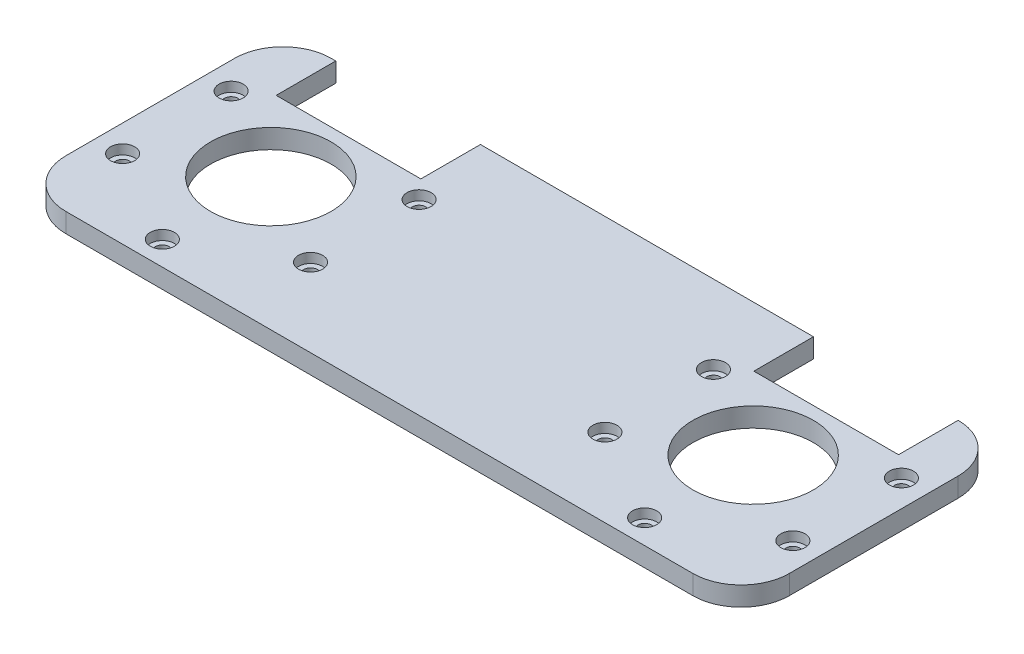
SolidWorks part; units mm, degrees
ref_plane "Front Plane" through (0, 0, 0) normal (0, 0, 1) x (1, 0, 0)
ref_plane "Top Plane" through (0, 0, 0) normal (0, 1, 0) x (1, 0, 0)
ref_plane "Right Plane" through (0, 0, 0) normal (1, 0, 0) x (0, 0, -1)
sketch "Sketch1" plane through (0, 0, 0) normal (0, 1, 0) x (1, 0, 0)
  line L0 (-50, 0) -> (50, 0) construction
  line L1 (-75, 27.5) -> (75, 27.5)
  line L2 (-75, 27.5) -> (-75, -27.5)
  line L3 (-75, -27.5) -> (75, -27.5)
  line L4 (75, 27.5) -> (75, -27.5)
  line L5 (0, 27.5) -> (0, 0) construction
  line L6 (0, 0) -> (0, -27.5) construction
  circle A0 centre (-50, 0) radius 12.5
  circle A1 centre (50, 0) radius 12.5
  dimension "D1" = 55
  dimension "D4" = 25
  dimension "D2" = 150
  dimension "D3" = 100
extrude "Boss-Extrude1" add sketch "Sketch1" along normal blind 4
sketch "Sketch2" plane through (0, 4, 0) normal (0, 1, 0) x (1, 0, 0)
  arc A0 (30.5144, -10.225) -> (30.5144, -12.275) centre (30.5144, -11.25) ccw construction
  arc A1 (30.5144, -10.225) -> (30.5144, -12.275) centre (30.5144, -11.25) ccw construction
  arc A2 (69.4856, -12.275) -> (69.4856, -10.225) centre (69.4856, -11.25) ccw construction
  arc A3 (69.4856, 10.225) -> (69.4856, 12.275) centre (69.4856, 11.25) ccw construction
  arc A4 (30.5144, 12.275) -> (30.5144, 10.225) centre (30.5144, 11.25) ccw construction
  arc A5 (50, -21.475) -> (50, -23.525) centre (50, -22.5) ccw construction
  arc A6 (69.4856, -12.275) -> (69.4856, -10.225) centre (69.4856, -11.25) ccw construction
  arc A7 (69.4856, 10.225) -> (69.4856, 12.275) centre (69.4856, 11.25) ccw construction
  arc A8 (30.5144, 12.275) -> (30.5144, 10.225) centre (30.5144, 11.25) ccw construction
  arc A9 (50, -21.475) -> (50, -23.525) centre (50, -22.5) ccw construction
  circle A10 centre (30.5144, 11.25) radius 1.4
  circle A11 centre (69.4856, 11.25) radius 1.4
  circle A12 centre (69.4856, -11.25) radius 1.4
  circle A13 centre (30.5144, -11.25) radius 1.4
  circle A14 centre (50, -22.5) radius 1.4
  dimension "D1" = 2.8
extrude "Cut-Extrude1" cut sketch "Sketch2" against normal through all
sketch "Sketch3" plane through (0, 4, 0) normal (0, 1, 0) x (1, 0, 0)
  circle A0 centre (30.5144, 11.25) radius 2.5
  circle A1 centre (30.5144, -11.25) radius 2.5
  circle A2 centre (50, -22.5) radius 2.5
  circle A3 centre (69.4856, -11.25) radius 2.5
  circle A4 centre (69.4856, 11.25) radius 2.5
  dimension "D1" = 5
extrude "Cut-Extrude3" cut sketch "Sketch3" against normal blind 2
mirror "Mirror1" about plane through (0, 0, 0) normal (1, 0, 0) of "Cut-Extrude3", "Cut-Extrude1"
fillet "Fillet1" radius 10 4 edges at (75, 2, -27.5) (75, 2, 27.5) (-75, 2, 27.5) (-75, 2, -27.5)
sketch "Sketch4" plane through (0, 0, 0) normal (0, -1, 0) x (1, 0, 0)
  line L0 (65, -27.5) -> (-65, -27.5) construction
  line L1 (-64.0407, -27.5) -> (-34.0407, -27.5)
  line L2 (-64.0407, -27.5) -> (-64.0407, -15.1427)
  line L3 (-64.0407, -15.1427) -> (-34.0407, -15.1427)
  line L4 (-34.0407, -27.5) -> (-34.0407, -15.1427)
  line L5 (35, -27.5) -> (65, -27.5)
  line L6 (35, -27.5) -> (35, -15.1427)
  line L7 (35, -15.1427) -> (65, -15.1427)
  line L8 (65, -27.5) -> (65, -15.1427)
  point P11 (65, -27.5)
  dimension "D1" = 30
  dimension "D2" = 12.3573
extrude "Cut-Extrude4" cut sketch "Sketch4" against normal through all
